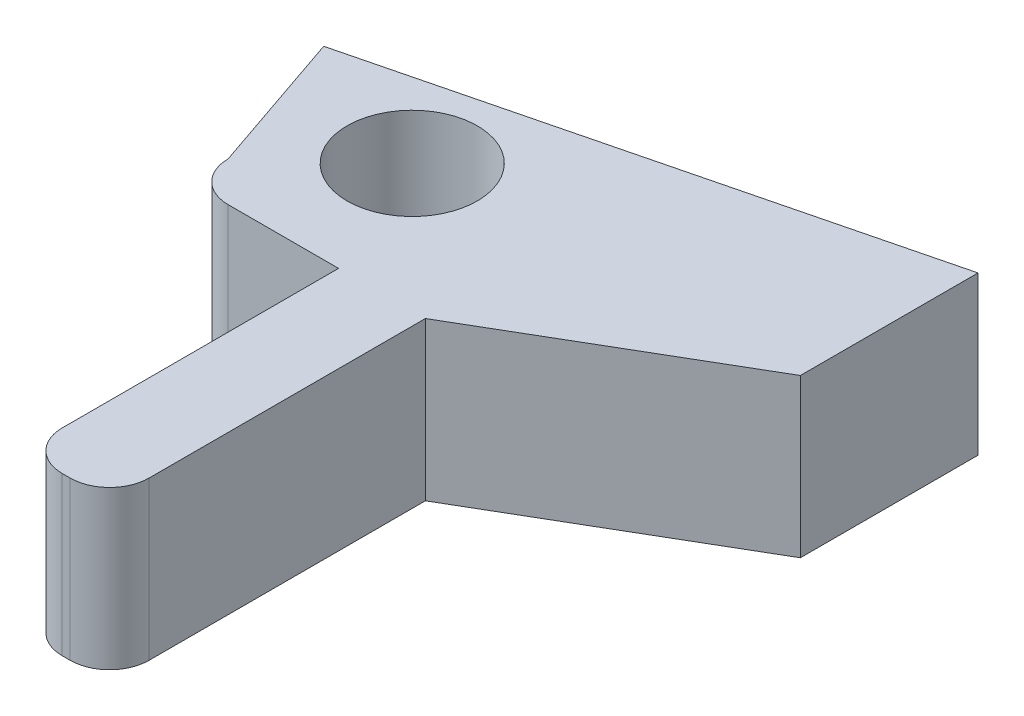
SolidWorks part; units mm, degrees
ref_plane "Front Plane" through (0, 0, 0) normal (0, 0, 1) x (1, 0, 0)
ref_plane "Top Plane" through (0, 0, 0) normal (0, 1, 0) x (1, 0, 0)
ref_plane "Right Plane" through (0, 0, 0) normal (1, 0, 0) x (0, 0, -1)
sketch "Sketch1" plane through (0, 0, 0) normal (0, 1, 0) x (1, 0, 0)
  line L0 (4.782, 3) -> (-7.218, 0)
  line L1 (4.782, 3) -> (4.782, 0)
  line L3 (-1.218, -5) -> (4.782, -1.5)
  line L5 (-7.218, 0) -> (-7.218, -5)
  line L6 (-7.218, -5) -> (-1.218, -5)
  line L7 (4.782, 0) -> (4.782, -1.5)
  circle A0 centre (-4.7887, -1.7635) radius 1.65
  dimension "D5" = 3.3
  dimension "D6" = 2.3
  dimension "D1" = 12
  dimension "D2" = 3
  dimension "D3" = 5
  dimension "D4" = 1.5
extrude "Boss-Extrude1" add sketch "Sketch1" along normal blind 4
sketch "Sketch2" plane through (0, 4, 0) normal (0, 1, 0) x (1, 0, 0)
  line L1 (-1.218, -5) -> (-3.418, -5)
  line L2 (-1.218, -5) -> (-1.218, -13)
  line L3 (-1.218, -13) -> (-3.418, -13)
  line L4 (-3.418, -5) -> (-3.418, -13)
  dimension "D1" = 8
  dimension "D2" = 2.2
extrude "Boss-Extrude2" add sketch "Sketch2" against normal blind 4
fillet "Fillet1" radius 1 2 edges at (-1.218, 2, 13) (-3.418, 2, 13)
fillet "Fillet2" radius 1 1 edges at (-7.218, 2, 5)
sketch "Sketch3" plane through (0, 4, 0) normal (0, 1, 0) x (1, 0, 0)
  line L0 (-7.218, 0) -> (-8.4792, -0.3153)
  line L1 (-8.4792, -0.3153) -> (-7.218, -4)
  line L2 (-7.218, -4) -> (-7.218, 0)
  dimension "D1" = 1.3
extrude "Boss-Extrude3" add sketch "Sketch3" against normal blind 4
